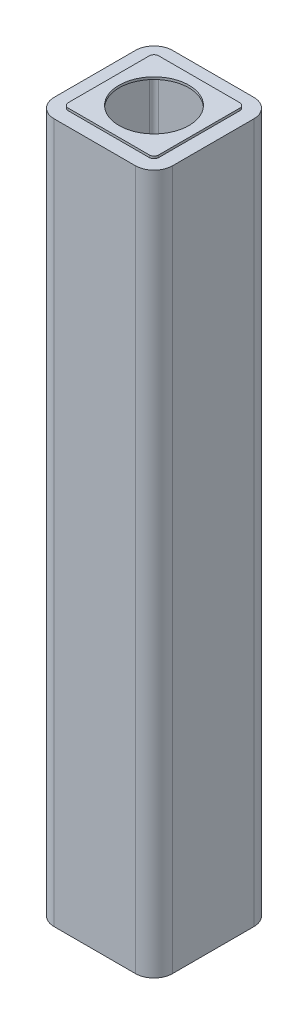
SolidWorks part; units mm, degrees
ref_plane "Front Plane" through (0, 0, 0) normal (0, 0, 1) x (1, 0, 0)
ref_plane "Top Plane" through (0, 0, 0) normal (0, 1, 0) x (1, 0, 0)
ref_plane "Right Plane" through (0, 0, 0) normal (1, 0, 0) x (0, 0, -1)
sketch3d "3DSketch1"
  line L0 (0, 0, 0) -> (0, 150, 0)
  dimension "D1" = 150
other "Square tube 20 X 20 X 2(1)"
ref_plane "Plane1" through (0, 0, 0) normal (0, 1, 0) x (1, 0, 0)
sketch "Sketch12" plane through (0, 0, 0) normal (0, 1, 0) x (1, 0, 0)
  line L0 (-8.7, -9.7) -> (8.7, -9.7)
  line L1 (-9.7, -8.7) -> (-9.7, 8.7)
  line L2 (8.7, 9.7) -> (-8.7, 9.7)
  line L3 (9.7, 8.7) -> (9.7, -8.7)
  line L4 (-8.7, -12.7) -> (8.7, -12.7)
  line L5 (-12.7, -8.7) -> (-12.7, 8.7)
  line L6 (8.7, 12.7) -> (-8.7, 12.7)
  line L7 (12.7, 8.7) -> (12.7, -8.7)
  arc A0 (12.7, 8.7) -> (8.7, 12.7) centre (8.7, 8.7) ccw
  arc A1 (8.7, -12.7) -> (12.7, -8.7) centre (8.7, -8.7) ccw
  arc A2 (-12.7, -8.7) -> (-8.7, -12.7) centre (-8.7, -8.7) ccw
  arc A3 (-8.7, 12.7) -> (-12.7, 8.7) centre (-8.7, 8.7) ccw
  arc A4 (-8.7, 9.7) -> (-9.7, 8.7) centre (-8.7, 8.7) ccw
  arc A5 (9.7, 8.7) -> (8.7, 9.7) centre (8.7, 8.7) ccw
  arc A6 (8.7, -9.7) -> (9.7, -8.7) centre (8.7, -8.7) ccw
  arc A7 (-9.7, -8.7) -> (-8.7, -9.7) centre (-8.7, -8.7) ccw
  point P0 (-12.7, 0)
  point P1 (12.7, 0)
  point P2 (0, 12.7)
  point P3 (0, -12.7)
  point P4 (0, 0)
  point P5 (-12.7, -12.7)
  point P6 (12.7, -12.7)
  point P7 (12.7, 12.7)
  point P8 (-12.7, 12.7)
  point P33 (0, 0)
  dimension "D1" = 4
  dimension "Thickness" = 3
  dimension "V_leg" = 25.4
sketch "Sketch13" plane through (0, 150, 0) normal (0, 1, 0) x (1, 0, 0)
  line L0 (9.7, -8.7) -> (9.7, 8.7) construction
  line L1 (-8.7, -9.7) -> (8.7, -9.7) construction
  line L2 (-9.7, 8.7) -> (-9.7, -8.7) construction
  line L3 (8.7, 9.7) -> (-8.7, 9.7) construction
  line L4 (9.7, -8.7) -> (9.7, 8.7)
  line L5 (-8.7, -9.7) -> (8.7, -9.7)
  line L6 (-9.7, 8.7) -> (-9.7, -8.7)
  line L7 (8.7, 9.7) -> (-8.7, 9.7)
  arc A0 (9.7, 8.7) -> (8.7, 9.7) centre (8.7, 8.7) ccw construction
  arc A1 (8.7, -9.7) -> (9.7, -8.7) centre (8.7, -8.7) ccw construction
  arc A2 (-9.7, -8.7) -> (-8.7, -9.7) centre (-8.7, -8.7) ccw construction
  arc A3 (-8.7, 9.7) -> (-9.7, 8.7) centre (-8.7, 8.7) ccw construction
  arc A4 (9.7, 8.7) -> (8.7, 9.7) centre (8.7, 8.7) ccw
  arc A5 (8.7, -9.7) -> (9.7, -8.7) centre (8.7, -8.7) ccw
  arc A6 (-9.7, -8.7) -> (-8.7, -9.7) centre (-8.7, -8.7) ccw
  arc A7 (-8.7, 9.7) -> (-9.7, 8.7) centre (-8.7, 8.7) ccw
  circle A8 centre (0, 0) radius 7.5
  dimension "D1" = 15
extrude "Boss-Extrude1" add sketch "Sketch13" along normal blind 0.5 separate body
